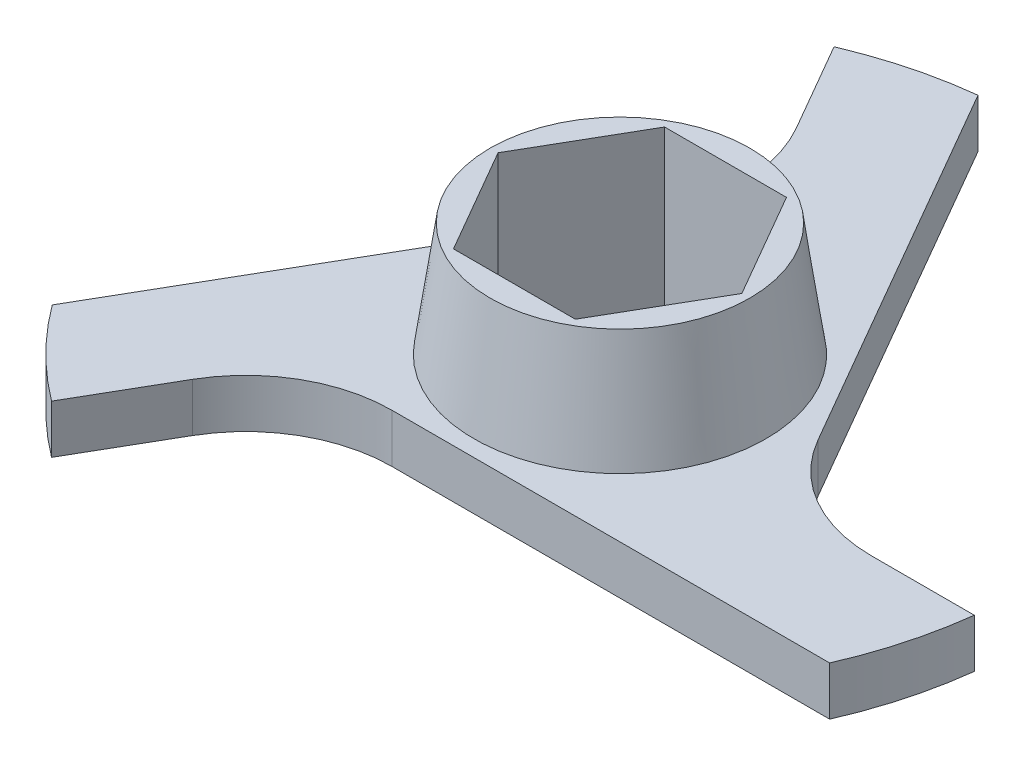
SolidWorks part; units mm, degrees
ref_plane "Front Plane" through (0, 0, 0) normal (0, 0, 1) x (1, 0, 0)
ref_plane "Top Plane" through (0, 0, 0) normal (0, 1, 0) x (1, 0, 0)
ref_plane "Right Plane" through (0, 0, 0) normal (1, 0, 0) x (0, 0, -1)
sketch "Sketch1" plane through (0, 0, 0) normal (0, 1, 0) x (1, 0, 0)
  line L0 (0, 20) -> (-2.7962, 24.8431)
  line L1 (0, 20) -> (-17.3205, -10)
  line L2 (-17.3205, -10) -> (17.3205, -10)
  line L3 (17.3205, -10) -> (0, 20)
  line L4 (0, 6) -> (-5.1962, -3) construction
  line L5 (-5.1962, -3) -> (5.1962, -3) construction
  line L6 (5.1962, -3) -> (0, 6) construction
  line L7 (0, 6) -> (-9.8116, 22.9942)
  circle A0 centre (0, 0) radius 10 construction
  circle A1 centre (0, 0) radius 3 construction
  circle A2 centre (0, 0) radius 25
  arc A3 (-6.6395, 8.5) -> (-6.6395, 17.5) centre (-14.4338, 13) ccw
  circle A4 centre (0, 0) radius 1.9
  dimension "D3" = 50
  dimension "D4" = 9
  dimension "D5" = 3.8
  dimension "D1" = 30
  dimension "D2" = 7
extrude "Boss-Extrude1" add sketch "Sketch1" along normal blind 10
pattern_circular "CirPattern1" count 3 over 360 about axis through (0, 0, 0) along (0, 1, 0) of "Boss-Extrude1"
sketch "Sketch3" plane through (0, 10, 0) normal (0, 1, 0) x (1, 0, 0)
  line L1 (3.7528, 6.5) -> (-3.7528, 6.5)
  line L2 (-3.7528, 6.5) -> (-7.5056, 0)
  line L3 (-7.5056, 0) -> (-3.7528, -6.5)
  line L4 (-3.7528, -6.5) -> (3.7528, -6.5)
  line L5 (3.7528, -6.5) -> (7.5056, 0)
  line L6 (7.5056, 0) -> (3.7528, 6.5)
  circle A0 centre (0, 0) radius 6.5 construction
  dimension "D1" = 13
extrude "Cut-Extrude1" cut sketch "Sketch3" against normal up to surface (10 mm away) up to face at (0, 0, 0)
sketch "Sketch5" plane through (0, 0, 0) normal (0, 0, 1) x (1, 0, 0)
  line L1 (-4.0415, 10) -> (22.9129, 10) construction
  line L2 (8, 10) -> (29.7596, 10)
  line L4 (0, 0) -> (0, 14.9469) construction
  line L5 (8, 10) -> (9, 3)
  line L6 (9, 3) -> (29.7596, 3)
  line L7 (29.7596, 3) -> (29.7596, 10)
  point P0 (29.7596, 3)
  dimension "D1" = 3
  dimension "D2" = 8
  dimension "D3" = 9
revolve "Cut-Revolve2" cut sketch "Sketch5" angle 360 about L4
